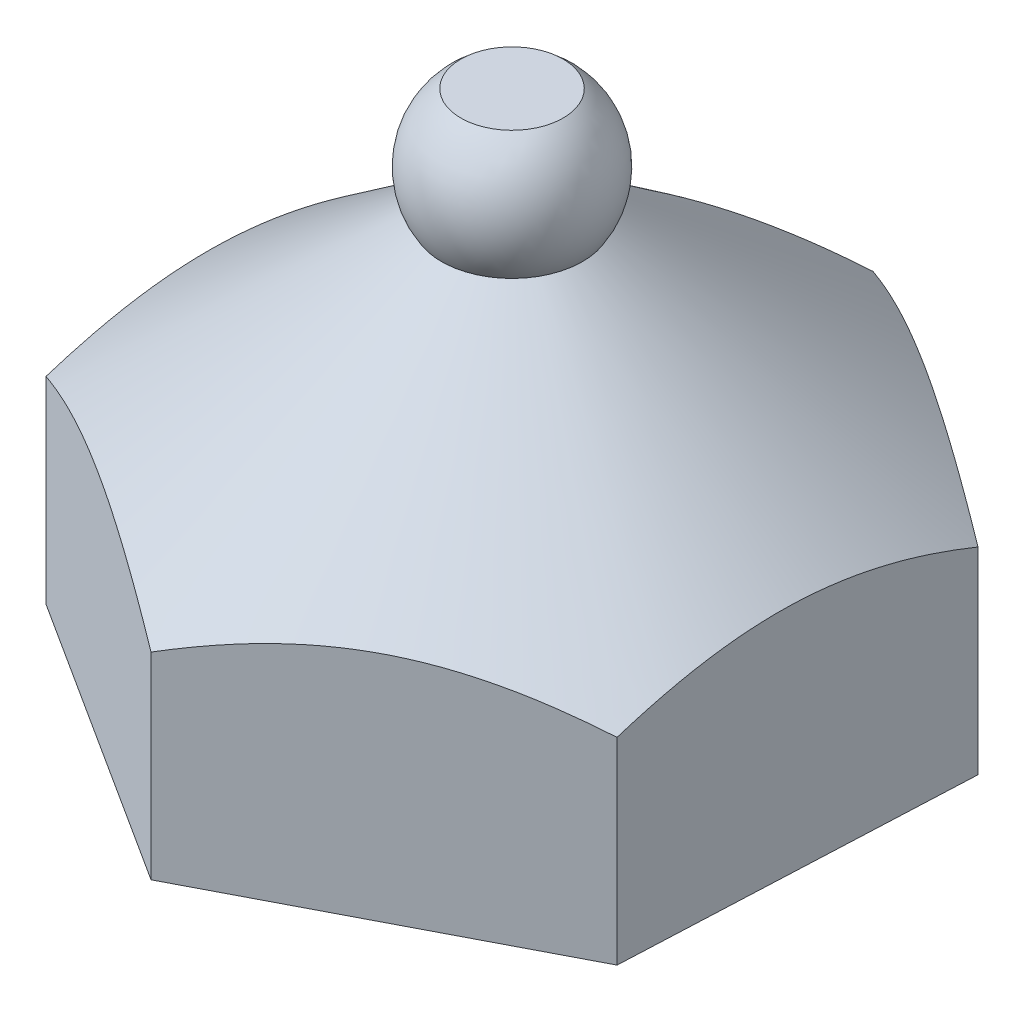
SolidWorks part; units mm, degrees
ref_plane "Front Plane" through (0, 0, 0) normal (0, 0, 1) x (1, 0, 0)
ref_plane "Top Plane" through (0, 0, 0) normal (0, 1, 0) x (1, 0, 0)
ref_plane "Right Plane" through (0, 0, 0) normal (1, 0, 0) x (0, 0, -1)
sketch "Sketch1" plane through (0, 0, 0) normal (0, 0, 1) x (1, 0, 0)
  line L0 (-7.1604, 51.1495) -> (-35.0476, 30)
  line L1 (-35.0476, 30) -> (-35.0476, 10)
  line L2 (-35.0476, 10) -> (-10, 10)
  line L3 (-10, 10) -> (-10, 0)
  line L4 (-10, 0) -> (0, 0)
  line L5 (0, 62.7619) -> (0, 0) construction
  line L6 (0, 62.7619) -> (-5.183, 62.7619)
  line L7 (0, 62.7619) -> (0, 0)
  arc A0 (-5.183, 62.7619) -> (-7.1604, 51.1495) centre (0, 55.9048) ccw
  dimension "D5" = 17.1911
  dimension "D1" = 10
  dimension "D2" = 10
  dimension "D3" = 20
  dimension "D4" = 35
  dimension "D6" = 5.183
  dimension "D7" = 62.7619
  dimension "D8" = 127.176
  dimension "D9" = 25.0476
revolve "Revolve1" add sketch "Sketch1" angle 360 about L5
sketch "Sketch2" plane through (0, 62.7619, 0) normal (0, 1, 0) x (1, 0, 0)
  line L1 (-31.113, -16.1344) -> (-1.5837, -35.0118)
  line L2 (-1.5837, -35.0118) -> (29.5293, -18.8774)
  line L3 (29.5293, -18.8774) -> (31.113, 16.1344)
  line L4 (31.113, 16.1344) -> (1.5837, 35.0118)
  line L5 (1.5837, 35.0118) -> (-29.5293, 18.8774)
  line L6 (-29.5293, 18.8774) -> (-31.113, -16.1344)
  circle A0 centre (0, 0) radius 30.3521 construction
extrude "Cut-Extrude1" cut sketch "Sketch2" against normal through all flip side to cut
chamfer "Chamfer1" distance 2 angle 45 1 edges at (-10, 0, 0)
